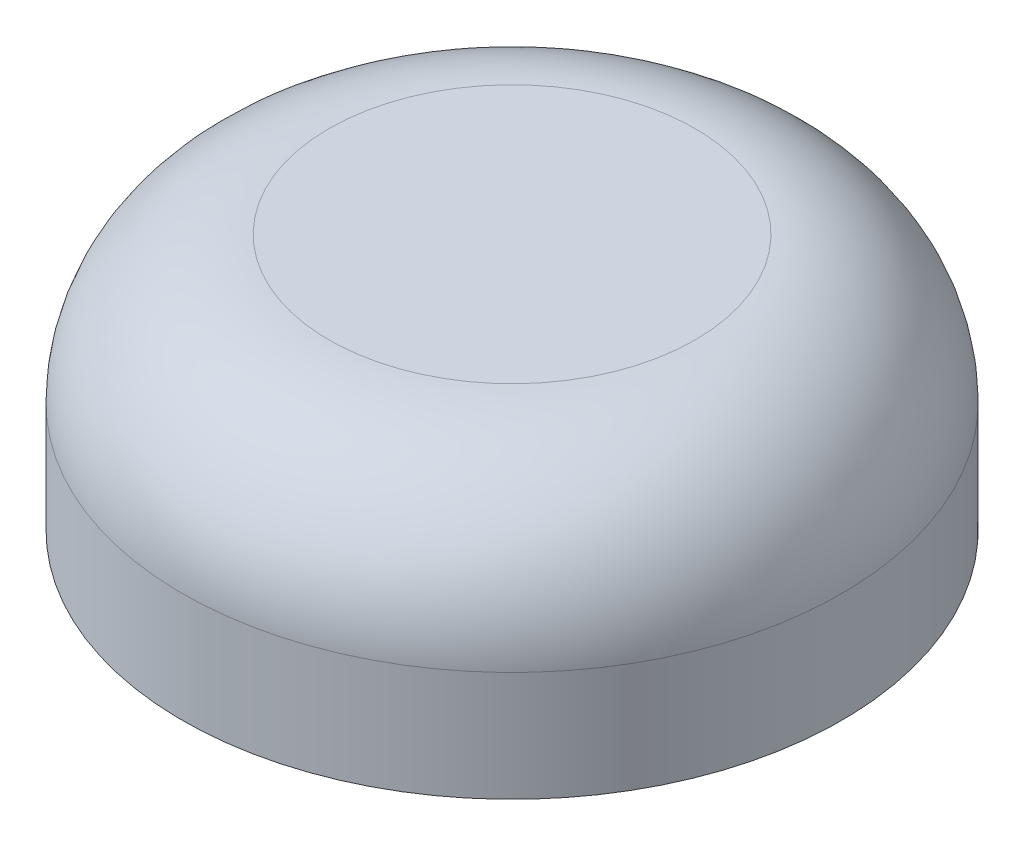
SolidWorks part; units mm, degrees
ref_plane "Piano frontale" through (0, 0, 0) normal (0, 0, 1) x (1, 0, 0)
ref_plane "Piano superiore" through (0, 0, 0) normal (0, 1, 0) x (1, 0, 0)
ref_plane "Piano destro" through (0, 0, 0) normal (1, 0, 0) x (0, 0, -1)
sketch "Schizzo1" plane through (0, 0, 0) normal (0, 0, 1) x (1, 0, 0)
  line L6 (0, 0) -> (1.5, 0)
  line L7 (1.5, 0) -> (1.5, -1.5)
  line L8 (1.5, -1.5) -> (4.5, -1.5)
  line L9 (4.5, -1.5) -> (4.5, 0)
  line L10 (2.5, 2) -> (0, 2)
  line L11 (0, 2) -> (0, 0)
  arc A0 (4.5, 0) -> (2.5, 2) centre (2.5, 0) ccw
  dimension "D5" = 2
  dimension "D1" = 1.5
  dimension "D2" = 3
  dimension "D3" = 1.5
  dimension "D4" = 2
revolve "Rivoluzione1" add sketch "Schizzo1" angle 360 about L11
